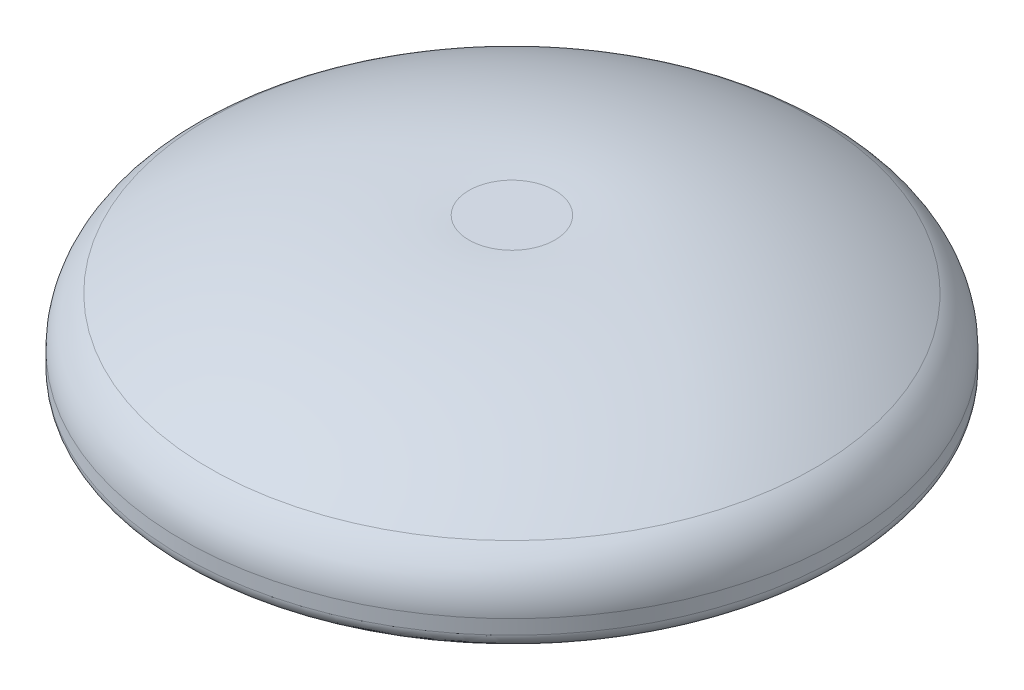
SolidWorks part; units mm, degrees
ref_plane "Front Plane" through (0, 0, 0) normal (0, 0, 1) x (1, 0, 0)
ref_plane "Top Plane" through (0, 0, 0) normal (0, 1, 0) x (1, 0, 0)
ref_plane "Right Plane" through (0, 0, 0) normal (1, 0, 0) x (0, 0, -1)
sketch "Sketch1" plane through (0, 0, 0) normal (0, 0, 1) x (1, 0, 0)
  line L0 (-11, 0) -> (-1, 0)
  line L1 (-1, 0) -> (-1, -5)
  line L2 (-1, -5) -> (0, -5)
  line L3 (0, 0) -> (0, 5.0624) construction
  line L4 (-11.5, 0.5) -> (-11.5, 1)
  line L5 (0, -5) -> (0, 5.0624)
  line L6 (-1.5, 5.0624) -> (0, 5.0624)
  arc A0 (-11.5, 0.5) -> (-11, 0) centre (-11, 0.5) ccw
  arc A2 (-10.565, 2.7003) -> (-1.5, 5.0624) centre (-2.3027, -10.4323) cw
  arc A3 (-11.5, 1) -> (-10.565, 2.7003) centre (-9.5, 1.0074) cw
  dimension "D1" = 0.5
  dimension "D3" = 2
  dimension "D2" = 0.5
  dimension "D4" = 0.9349
  dimension "D5" = 2.7003
  dimension "D6" = 5.0624
  dimension "D7" = 9.065
  dimension "D8" = 1.5
  dimension "D9" = 1
  dimension "D10" = 10
  dimension "D11" = 5.0624
revolve "Revolve1" add sketch "Sketch1" angle 360 about L3
fillet "Fillet1" radius 1.5 1 edges at (0, 0, -1)
chamfer "Chamfer1" distance 0.5 angle 45 1 edges at (0, -5, -1)
